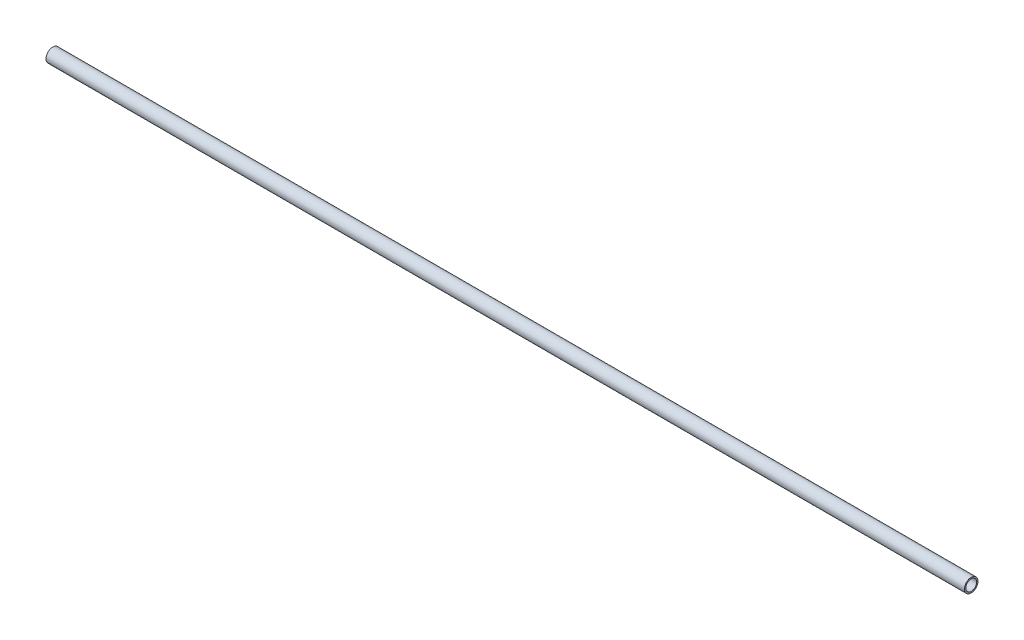
SolidWorks part; units mm, degrees
material "windcatcher"
ref_plane "Front Plane" through (0, 0, 0) normal (0, 0, 1) x (1, 0, 0)
ref_plane "Top Plane" through (0, 0, 0) normal (0, 1, 0) x (1, 0, 0)
ref_plane "Right Plane" through (0, 0, 0) normal (1, 0, 0) x (0, 0, -1)
sketch "Sketch1" plane through (0, 0, 0) normal (1, 0, 0) x (0, 0, -1)
  circle A0 centre (0, 0) radius 5
  circle A1 centre (0, 0) radius 4
  dimension "D1" = 10
  dimension "D2" = 8
extrude "Boss-Extrude1" add sketch "Sketch1" along normal mid plane 675
